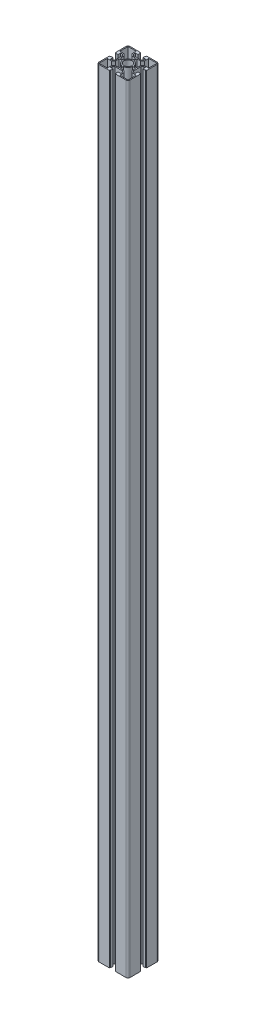
SolidWorks part; units mm, degrees
ref_plane "前视基准面" through (0, 0, 0) normal (0, 0, 1) x (1, 0, 0)
ref_plane "上视基准面" through (0, 0, 0) normal (0, 1, 0) x (1, 0, 0)
ref_plane "右视基准面" through (0, 0, 0) normal (1, 0, 0) x (0, 0, -1)
sketch "草图1" plane through (0, 0, 0) normal (0, 1, 0) x (1, 0, 0)
  line L0 (0, 32.6515) -> (0, -47.5) construction
  line L2 (-54.5455, 0) -> (57.7273, 0) construction
  line L82 (-16, 1) -> (-9.9499, 1)
  line L83 (-30, 6) -> (-28.5, 6)
  line L88 (-16, 1) -> (-16, 7.8284)
  line L89 (-16, 7.8284) -> (-20.1716, 12)
  line L90 (-20.1716, 12) -> (-28, 12)
  line L91 (-28, 12) -> (-28, 28)
  line L92 (-28, 28) -> (-12, 28)
  line L93 (-12, 28) -> (-12, 20.1716)
  line L94 (-12, 20.1716) -> (-7.8284, 16)
  line L95 (-7.8284, 16) -> (-1, 16)
  line L96 (-1, 16) -> (-1, 9.9499)
  line L97 (1, 9.9499) -> (1, 16)
  line L98 (1, 16) -> (7.8284, 16)
  line L99 (7.8284, 16) -> (12, 20.1716)
  line L100 (12, 20.1716) -> (12, 28)
  line L101 (12, 28) -> (28, 28)
  line L102 (28, 28) -> (28, 12)
  line L103 (28, 12) -> (20.1716, 12)
  line L104 (20.1716, 12) -> (16, 7.8284)
  line L105 (16, 7.8284) -> (16, 1)
  line L106 (16, 1) -> (9.9499, 1)
  line L107 (9.9499, -1) -> (16, -1)
  line L108 (16, -1) -> (16, -7.8284)
  line L109 (16, -7.8284) -> (20.1716, -12)
  line L110 (20.1716, -12) -> (28, -12)
  line L111 (28, -12) -> (28, -28)
  line L112 (28, -28) -> (12, -28)
  line L113 (12, -28) -> (12, -20.1716)
  line L114 (12, -20.1716) -> (7.8284, -16)
  line L115 (7.8284, -16) -> (1, -16)
  line L116 (1, -16) -> (1, -9.9499)
  line L117 (-1, -9.9499) -> (-1, -16)
  line L118 (-1, -16) -> (-7.8284, -16)
  line L119 (-7.8284, -16) -> (-12, -20.1716)
  line L120 (-12, -20.1716) -> (-12, -28)
  line L121 (-12, -28) -> (-28, -28)
  line L122 (-28, -28) -> (-28, -12)
  line L123 (-28, -12) -> (-20.1716, -12)
  line L124 (-20.1716, -12) -> (-16, -7.8284)
  line L125 (-16, -7.8284) -> (-16, -1)
  line L126 (-28.5, 6) -> (-28.5, 5)
  line L127 (-28.5, 5) -> (-24, 5)
  line L128 (-24, 5) -> (-24, 10)
  line L129 (-24, 10) -> (-21, 10)
  line L130 (-21, 10) -> (-18, 7)
  line L131 (-18, 7) -> (-18, -7)
  line L132 (-18, -7) -> (-21, -10)
  line L133 (-21, -10) -> (-24, -10)
  line L134 (-24, -10) -> (-24, -5)
  line L135 (-24, -5) -> (-28.5, -5)
  line L136 (-28.5, -5) -> (-28.5, -6)
  line L137 (-28.5, -6) -> (-30, -6)
  line L138 (-30, -6) -> (-30, -26)
  line L139 (-26, -30) -> (-6, -30)
  line L140 (-6, -30) -> (-6, -28.5)
  line L141 (-6, -28.5) -> (-5, -28.5)
  line L142 (-5, -28.5) -> (-5, -24)
  line L143 (-5, -24) -> (-10, -24)
  line L144 (-10, -24) -> (-10, -21)
  line L145 (-10, -21) -> (-7, -18)
  line L146 (-7, -18) -> (7, -18)
  line L147 (7, -18) -> (10, -21)
  line L148 (10, -21) -> (10, -24)
  line L149 (10, -24) -> (5, -24)
  line L150 (5, -24) -> (5, -28.5)
  line L151 (5, -28.5) -> (6, -28.5)
  line L152 (6, -28.5) -> (6, -30)
  line L153 (6, -30) -> (26, -30)
  line L154 (30, -26) -> (30, -6)
  line L155 (30, -6) -> (28.5, -6)
  line L156 (28.5, -6) -> (28.5, -5)
  line L157 (28.5, -5) -> (24, -5)
  line L158 (24, -5) -> (24, -10)
  line L159 (24, -10) -> (21, -10)
  line L160 (21, -10) -> (18, -7)
  line L161 (18, -7) -> (18, 7)
  line L162 (18, 7) -> (21, 10)
  line L163 (21, 10) -> (24, 10)
  line L164 (24, 10) -> (24, 5)
  line L165 (24, 5) -> (28.5, 5)
  line L166 (28.5, 5) -> (28.5, 6)
  line L167 (28.5, 6) -> (30, 6)
  line L168 (30, 6) -> (30, 26)
  line L169 (26, 30) -> (6, 30)
  line L170 (6, 30) -> (6, 28.5)
  line L171 (6, 28.5) -> (5, 28.5)
  line L172 (5, 28.5) -> (5, 24)
  line L173 (5, 24) -> (10, 24)
  line L174 (10, 24) -> (10, 21)
  line L175 (10, 21) -> (7, 18)
  line L176 (7, 18) -> (-7, 18)
  line L177 (-7, 18) -> (-10, 21)
  line L178 (-10, 21) -> (-10, 24)
  line L179 (-10, 24) -> (-5, 24)
  line L180 (-5, 24) -> (-5, 28.5)
  line L181 (-5, 28.5) -> (-6, 28.5)
  line L182 (-6, 28.5) -> (-6, 30)
  line L183 (-6, 30) -> (-26, 30)
  line L184 (-30, 26) -> (-30, 6)
  line L185 (-16, -1) -> (-9.9499, -1)
  arc A41 (-9.9499, -1) -> (-1, -9.9499) centre (0, 0) ccw
  circle A42 centre (0, 0) radius 8
  arc A43 (-26, -30) -> (-30, -26) centre (-26, -26) cw
  arc A44 (26, 30) -> (30, 26) centre (26, 26) cw
  arc A45 (-26, 30) -> (-30, 26) centre (-26, 26) ccw
  arc A46 (26, -30) -> (30, -26) centre (26, -26) ccw
  arc A47 (9.9499, 1) -> (1, 9.9499) centre (0, 0) ccw
  arc A48 (-1, 9.9499) -> (-9.9499, 1) centre (0, 0) ccw
  arc A49 (1, -9.9499) -> (9.9499, -1) centre (0, 0) ccw
extrude "凸台-拉伸1" add sketch "草图1" along normal blind 1500
ref_plane "基准面2" through (0, 738, 0) normal (0, 1, 0) x (1, 0, 0)
